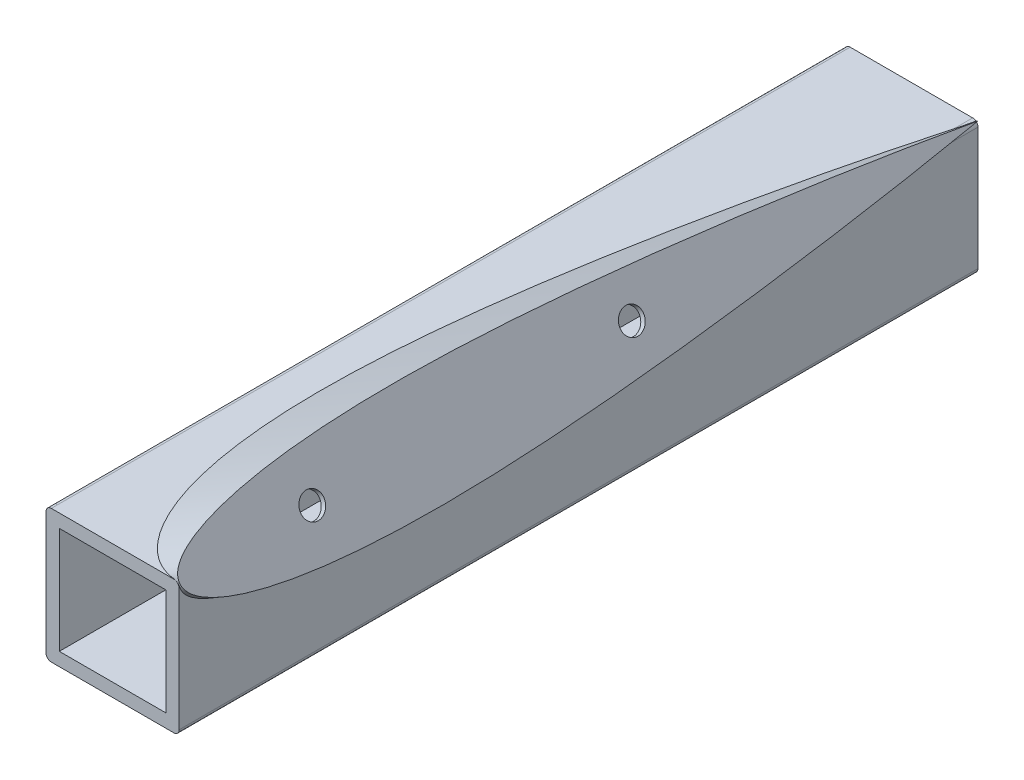
SolidWorks part; units mm, degrees
ref_plane "Front Plane" through (0, 0, 0) normal (0, 0, 1) x (1, 0, 0)
ref_plane "Top Plane" through (0, 0, 0) normal (0, 1, 0) x (1, 0, 0)
ref_plane "Right Plane" through (0, 0, 0) normal (1, 0, 0) x (0, 0, -1)
sketch "Sketch1" plane through (0, 0, 0) normal (0, 0, 1) x (1, 0, 0)
  line L1 (-12.5, 12.5) -> (12.5, 12.5)
  line L2 (-12.5, 12.5) -> (-12.5, -12.5)
  line L3 (-12.5, -12.5) -> (12.5, -12.5)
  line L4 (12.5, 12.5) -> (12.5, -12.5)
  line L5 (-12.5, 12.5) -> (12.5, -12.5) construction
  line L6 (-12.5, -12.5) -> (12.5, 12.5) construction
  point P0 (0, 0)
  dimension "D1" = 25
  dimension "D2" = 25
extrude "Boss-Extrude1" add sketch "Sketch1" along normal blind 150 contours L2 L3 L4 L1
ref_plane "Plane2" through (14.7877, 8.5377, 0) normal (-0.866, -0.5, 0) x (0, 0, -1)
sketch "Sketch3" plane through (14.7877, 8.5377, 0) normal (-0.866, -0.5, 0) x (0, 0, -1)
  line L0 (-150, -4.5753) -> (0, -4.5753) construction
  line L1 (-150, -4.5753) -> (0, -4.5753)
fillet "Fillet1" radius 1 4 edges at (-12.5, -12.5, 75) (12.5, 12.5, 75) (12.5, -12.5, 75) (-12.5, 12.5, 75)
sketch "Sketch5" plane through (14.7877, 8.5377, 0) normal (-0.866, -0.5, 0) x (0, 0, -1)
  line L0 (-150, -4.5753) -> (-149, -4.5741) construction
  line L1 (-150, -4.5753) -> (0, -4.5753) construction
  spline S0 degree 3 poles (-150, -4.5753) (-149.9999, -4.5768) (-149.9996, -4.5797) (-149.9977, -4.584) (-149.9947, -4.5881) (-149.9905, -4.592) (-149.9852, -4.5959) (-149.9788, -4.5996) (-149.9713, -4.6031) (-149.9627, -4.6066) (-149.9531, -4.6099) (-149.9423, -4.613) (-149.9261, -4.617) (-149.9033, -4.6216) (-149.873, -4.626) (-149.8394, -4.6296) (-149.8025, -4.6322) (-149.7556, -4.6342) (-149.6981, -4.6349) (-149.6303, -4.6337) (-149.5516, -4.6304) (-149.464, -4.6248) (-149.3701, -4.6171) (-149.2747, -4.6078) (-149.1791, -4.5974) (-149.0895, -4.5864) (-149.0305, -4.5784) (-149.0033, -4.5745) (-149.0002, -4.5741) (-149, -4.5741) knots 0 0 0 0 0.004218 0.008652 0.013562 0.019137 0.0255 0.032726 0.040862 0.04993 0.05994 0.070892 0.082777 0.109286 0.139301 0.172602 0.208924 0.247965 0.310881 0.377906 0.447679 0.542484 0.636087 0.724985 0.82444 0.919093 0.990775 0.999422 1 1 1 1 construction
  spline S2 degree 3 poles (-150, -4.5753) (-149.9999, -4.5739) (-149.9996, -4.5709) (-149.9977, -4.5667) (-149.9947, -4.5625) (-149.9906, -4.5586) (-149.9853, -4.5547) (-149.9789, -4.551) (-149.9714, -4.5474) (-149.9628, -4.544) (-149.9532, -4.5407) (-149.9424, -4.5375) (-149.9262, -4.5334) (-149.9034, -4.5288) (-149.8732, -4.5243) (-149.8395, -4.5207) (-149.8027, -4.5179) (-149.7557, -4.5158) (-149.6983, -4.515) (-149.6304, -4.516) (-149.5518, -4.5191) (-149.4642, -4.5245) (-149.3702, -4.532) (-149.2748, -4.541) (-149.1792, -4.5512) (-149.0895, -4.562) (-149.0305, -4.5698) (-149.0033, -4.5736) (-149.0002, -4.574) (-149, -4.5741) knots 0 0 0 0 0.004218 0.008652 0.013562 0.019137 0.0255 0.032726 0.040862 0.04993 0.05994 0.070892 0.082777 0.109286 0.139301 0.172602 0.208924 0.247965 0.310881 0.377906 0.447679 0.542484 0.636087 0.724985 0.82444 0.919093 0.990775 0.999422 1 1 1 1 construction
  spline S3 degree 3 poles (-150, -4.5753) (-149.9823, -4.3597) (-149.9459, -3.9173) (-149.6568, -3.2765) (-149.2065, -2.6599) (-148.5814, -2.0649) (-147.7896, -1.4895) (-146.8302, -0.933) (-145.7052, -0.3962) (-144.4166, 0.1198) (-142.9668, 0.6135) (-141.359, 1.0831) (-138.9191, 1.6976) (-135.4976, 2.3801) (-130.9667, 3.0525) (-125.9153, 3.5942) (-120.3897, 3.998) (-113.3466, 4.3089) (-104.7314, 4.4192) (-94.5508, 4.2487) (-82.7528, 3.7713) (-69.6159, 2.9496) (-55.5249, 1.8061) (-41.2158, 0.4403) (-26.8721, -1.114) (-13.4209, -2.7471) (-4.5792, -3.9305) (-0.4948, -4.5053) (-0.0292, -4.5712) (0, -4.5753) knots 0 0 0 0 0.004218 0.008652 0.013562 0.019137 0.0255 0.032726 0.040862 0.04993 0.05994 0.070892 0.082777 0.109286 0.139301 0.172602 0.208924 0.247965 0.310881 0.377906 0.447679 0.542484 0.636087 0.724985 0.82444 0.919093 0.990775 0.999422 1 1 1 1
  spline S4 degree 3 poles (-150, -4.5753) (-149.9823, -4.7909) (-149.9459, -5.2333) (-149.6568, -5.8742) (-149.2065, -6.4908) (-148.5814, -7.0857) (-147.7896, -7.6612) (-146.8302, -8.2176) (-145.7052, -8.7544) (-144.4166, -9.2705) (-142.9668, -9.7641) (-141.359, -10.2337) (-138.9191, -10.8482) (-135.4976, -11.5308) (-130.9667, -12.2031) (-125.9153, -12.7448) (-120.3897, -13.1487) (-113.3466, -13.4595) (-104.7314, -13.5698) (-94.5508, -13.3993) (-82.7528, -12.9219) (-69.6159, -12.1002) (-55.5249, -10.9567) (-41.2158, -9.5909) (-26.8721, -8.0366) (-13.4209, -6.4035) (-4.5792, -5.2201) (-0.4948, -4.6454) (-0.0292, -4.5795) (0, -4.5753) knots 0 0 0 0 0.004218 0.008652 0.013562 0.019137 0.0255 0.032726 0.040862 0.04993 0.05994 0.070892 0.082777 0.109286 0.139301 0.172602 0.208924 0.247965 0.310881 0.377906 0.447679 0.542484 0.636087 0.724985 0.82444 0.919093 0.990775 0.999422 1 1 1 1
  dimension "D1" = 150
extrude "Boss-Extrude2" add sketch "Sketch5" along normal blind 20
sketch "Sketch6" plane through (0, 0, 0) normal (0, 0, 1) x (1, 0, 0)
  line L0 (-11.5, 12.5) -> (11.5, 12.5) construction
  line L1 (10, 10) -> (-10, 10)
  line L2 (10, 10) -> (10, -10)
  line L3 (10, -10) -> (-10, -10)
  line L4 (-10, 10) -> (-10, -10)
  line L5 (-11.5, -12.5) -> (11.5, -12.5) construction
  line L6 (-12.5, 11.5) -> (-12.5, -11.5) construction
  line L7 (12.5, 11.5) -> (12.5, -11.5) construction
  dimension "D1" = 2.5
  dimension "D2" = 2.5
  dimension "D3" = 2.5
  dimension "D4" = 2.5
extrude "Cut-Extrude1" cut sketch "Sketch6" along normal blind 150
sketch "Sketch7" plane through (14.7877, 8.5377, 0) normal (-0.866, -0.5, 0) x (0, 0, -1)
  line L0 (-120, -4.5753) -> (-130, -4.5753) construction
  line L1 (-130, 0.4247) -> (-120, 0.4247)
  line L2 (-130, 0.4247) -> (-130, -9.5753)
  line L3 (-130, -9.5753) -> (-120, -9.5753)
  line L4 (-120, 0.4247) -> (-120, -9.5753)
  line L5 (-150, -4.5753) -> (0, -4.5753) construction
  line L6 (-60, -4.5753) -> (-70, -4.5753) construction
  line L7 (-70, 0.4247) -> (-60, 0.4247)
  line L8 (-70, 0.4247) -> (-70, -9.5753)
  line L9 (-70, -9.5753) -> (-60, -9.5753)
  line L10 (-60, 0.4247) -> (-60, -9.5753)
  point P15 (0, 0)
  point P16 (0, 0)
  dimension "D1" = 10
  dimension "D2" = 20
  dimension "D3" = 10
  dimension "D4" = 50
ref_plane "Plane3" through (11.8301, 6.8301, 0) normal (-0.866, -0.5, 0) x (0, 0, 1)
sketch "Sketch9" plane through (11.8301, 6.8301, 0) normal (-0.866, -0.5, 0) x (0, 0, 1)
  line L0 (70, -0.4247) -> (60, -0.4247) construction
  line L1 (60, -0.4247) -> (60, 9.5753) construction
  line L2 (70, 9.5753) -> (60, 9.5753) construction
  line L3 (70, -0.4247) -> (70, 9.5753) construction
  line L4 (120, -0.4247) -> (120, 9.5753) construction
  line L5 (130, -0.4247) -> (130, 9.5753) construction
  line L6 (130, -0.4247) -> (120, -0.4247) construction
  line L7 (130, 9.5753) -> (120, 9.5753) construction
  line L8 (70, -0.4247) -> (60, -0.4247)
  line L9 (60, -0.4247) -> (60, 9.5753)
  line L10 (70, 9.5753) -> (60, 9.5753)
  line L11 (70, -0.4247) -> (70, 9.5753)
  line L12 (120, -0.4247) -> (120, 9.5753)
  line L13 (130, -0.4247) -> (130, 9.5753)
  line L14 (130, -0.4247) -> (120, -0.4247)
  line L15 (130, 9.5753) -> (120, 9.5753)
extrude "Cut-Extrude3" cut sketch "Sketch9" along normal up to vertex
sketch "Sketch13" plane through (11.8301, 6.8301, 0) normal (-0.866, -0.5, 0) x (0, 0, 1)
  line L0 (60, 9.5753) -> (70, -0.4247)
  line L1 (60, -0.4247) -> (70, 9.5753)
sketch "Sketch15" plane through (11.8301, 6.8301, 0) normal (-0.866, -0.5, 0) x (0, 0, 1)
  line L0 (120, 9.5753) -> (130, -0.4247)
  line L1 (120, -0.4247) -> (130, 9.5753)
hole_wizard "CSK for M4 Countersunk Flat Head Screw1" positions "Sketch24" profile "Sketch25" countersink size "M4" standard "ISO" end condition through all
sketch "Sketch24" plane through (11.8301, 6.8301, 0) normal (-0.866, -0.5, 0) x (0, 0, 1)
  line L0 (120, 9.5753) -> (130, -0.4247) construction
  point P0 (125, 4.5753)
sketch "Sketch25" plane through (9.5425, 10.7925, 125) normal (0, 0, 1) x (0.5, -0.866, 0)
  line L0 (0, 0) -> (0, 11.6643)
  line L1 (0, 11.6643) -> (2.25, 11.6643)
  line L2 (2.25, 11.6643) -> (2.25, 2.45)
  line L3 (2.25, 2.45) -> (4.7, 0)
  line L5 (4.7, 0) -> (0, 0)
  line L6 (-2.25, 2.45) -> (-4.7, 0) construction
  line L11 (0, -6.35) -> (0, 107.95) construction
  dimension "Thru Hole Dia." = 4.5
  dimension "Thru Hole Depth" = 11.6643
  dimension "Near C'Sink Dia." = 9.4
  dimension "Near C'Sink Angle" = 90
hole_wizard "CSK for M4 Countersunk Flat Head Screw2" positions "Sketch27" profile "Sketch28" countersink size "M4" standard "ISO" end condition through all
sketch "Sketch27" plane through (11.8301, 6.8301, 0) normal (-0.866, -0.5, 0) x (0, 0, 1)
  point P0 (65, 4.5756)
sketch "Sketch28" plane through (9.5423, 10.7927, 65) normal (0, 0, 1) x (0.5, -0.866, 0)
  line L0 (0, 0) -> (0, 11.6643)
  line L1 (0, 11.6643) -> (2.25, 11.6643)
  line L2 (2.25, 11.6643) -> (2.25, 2.45)
  line L3 (2.25, 2.45) -> (4.7, 0)
  line L5 (4.7, 0) -> (0, 0)
  line L6 (-2.25, 2.45) -> (-4.7, 0) construction
  line L11 (0, -6.35) -> (0, 107.95) construction
  dimension "Thru Hole Dia." = 4.5
  dimension "Thru Hole Depth" = 11.6643
  dimension "Near C'Sink Dia." = 9.4
  dimension "Near C'Sink Angle" = 90
